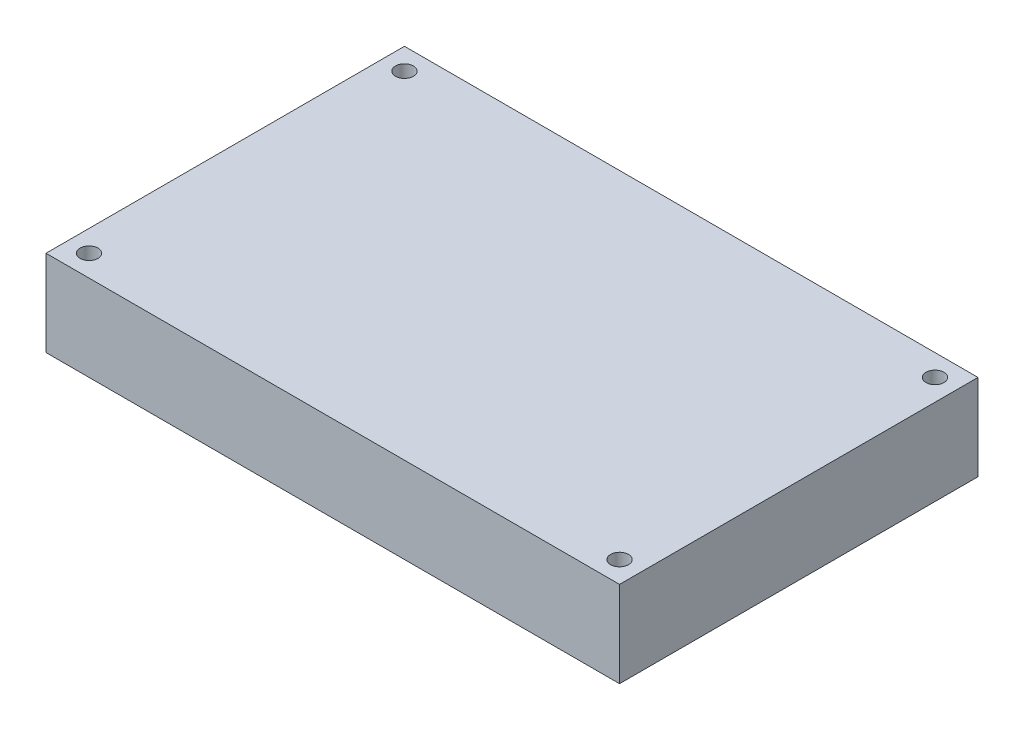
SolidWorks part; units mm, degrees
ref_plane "Front Plane" through (0, 0, 0) normal (0, 0, 1) x (1, 0, 0)
ref_plane "Top Plane" through (0, 0, 0) normal (0, 1, 0) x (1, 0, 0)
ref_plane "Right Plane" through (0, 0, 0) normal (1, 0, 0) x (0, 0, -1)
sketch "Sketch1" plane through (0, 0, 0) normal (0, 1, 0) x (1, 0, 0)
  line L1 (-40, 25) -> (40, 25)
  line L2 (-40, 25) -> (-40, -25)
  line L3 (-40, -25) -> (40, -25)
  line L4 (40, 25) -> (40, -25)
  line L5 (-40, 25) -> (40, -25) construction
  line L6 (-40, -25) -> (40, 25) construction
  line L7 (-37, 22) -> (37, 22) construction
  line L8 (-37, 22) -> (-37, -22) construction
  line L9 (-37, -22) -> (37, -22) construction
  line L10 (37, 22) -> (37, -22) construction
  line L11 (-37, 22) -> (37, -22) construction
  line L12 (-37, -22) -> (37, 22) construction
  circle A0 centre (-37, 22) radius 1.25
  circle A1 centre (37, 22) radius 1.25
  circle A2 centre (37, -22) radius 1.25
  circle A3 centre (-37, -22) radius 1.25
  point P0 (0, 0)
  point P5 (0, 0)
  dimension "D5" = 2.5
  dimension "D6" = 2.5
  dimension "D7" = 2.5
  dimension "D8" = 2.5
  dimension "D1" = 50
  dimension "D2" = 80
  dimension "D3" = 44
  dimension "D4" = 74
extrude "Boss-Extrude1" add sketch "Sketch1" along normal blind 12
